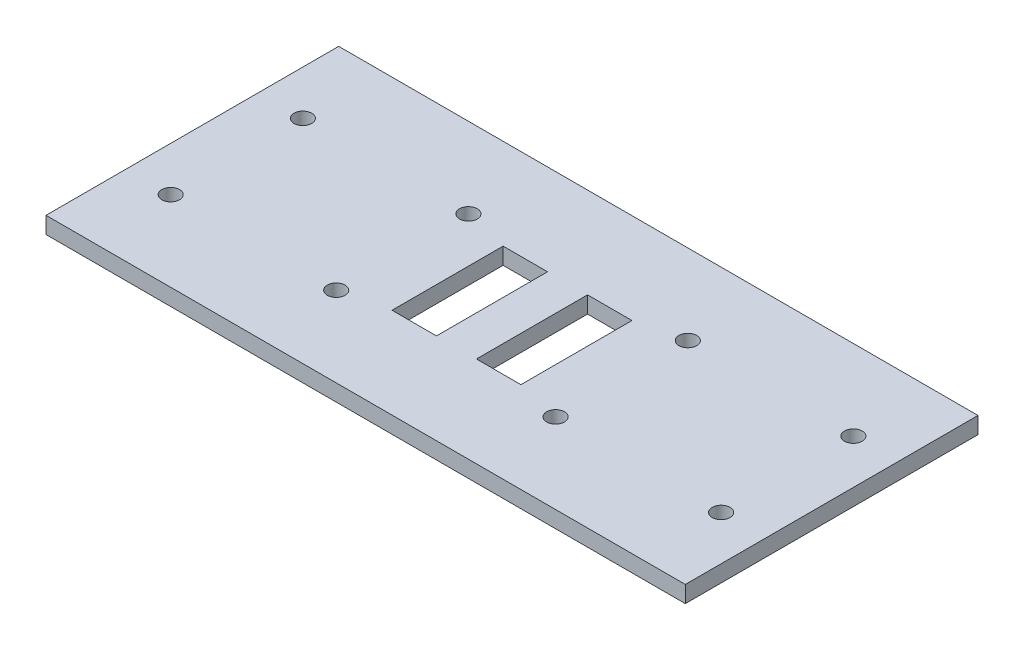
SolidWorks part; units mm, degrees
ref_plane "Plano frontal" through (0, 0, 0) normal (0, 0, 1) x (1, 0, 0)
ref_plane "Plano superior" through (0, 0, 0) normal (0, 1, 0) x (1, 0, 0)
ref_plane "Plano direito" through (0, 0, 0) normal (1, 0, 0) x (0, 0, -1)
sketch "Esboço1" plane through (0, 0, 0) normal (0, 1, 0) x (1, 0, 0)
  line L7 (-57.5484, 26.3464) -> (57.5484, 26.3464)
  line L8 (57.5484, 26.3464) -> (57.5484, -26.3464)
  line L9 (57.5484, -26.3464) -> (-57.5484, -26.3464)
  line L10 (-57.5484, -26.3464) -> (-57.5484, 26.3464)
  line L11 (0, 26.3464) -> (0, -26.3464) construction
  line L12 (-57.5484, 0) -> (57.5484, 0) construction
extrude "Ressalto-extrusão1" add sketch "Esboço1" along normal blind 3
sketch "Esboço2" plane through (0, 3, 0) normal (0, 1, 0) x (1, 0, 0)
  line L0 (0, 26.3464) -> (0, -26.3464) construction
  line L1 (57.5484, 26.3464) -> (-57.5484, 26.3464) construction
  line L2 (-57.5484, -26.3464) -> (57.5484, -26.3464) construction
  circle A0 centre (-49.5484, 11.9) radius 1.6
  circle A1 centre (-19.7484, 11.9) radius 1.6
  circle A2 centre (-49.5484, -11.9) radius 1.6
  circle A3 centre (-19.7484, -11.9) radius 1.6
  circle A4 centre (49.5484, -11.9) radius 1.6
  circle A5 centre (19.7484, -11.9) radius 1.6
  circle A6 centre (19.7484, 11.9) radius 1.6
  circle A7 centre (49.5484, 11.9) radius 1.6
extrude "Corte-extrusão1" cut sketch "Esboço2" against normal through all
sketch "Esboço3" plane through (0, 3, 0) normal (0, 1, 0) x (1, 0, 0)
  line L0 (-13.3484, 18.5) -> (-1.8484, 18.5) construction
  line L1 (-1.8484, 18.5) -> (-1.8484, -18.5) construction
  line L2 (-11.5984, 10) -> (-3.5984, 10)
  line L3 (-3.5984, 10) -> (-3.5984, -10)
  line L4 (-3.5984, -10) -> (-11.5984, -10)
  line L5 (-11.5984, -10) -> (-11.5984, 10)
  line L7 (0, 0) -> (0, -26.3464) construction
  line L8 (-57.5484, -26.3464) -> (57.5484, -26.3464) construction
  line L9 (3.5984, -10) -> (11.5984, -10)
  line L10 (3.5984, 10) -> (3.5984, -10)
  line L11 (11.5984, -10) -> (11.5984, 10)
  line L12 (11.5984, 10) -> (3.5984, 10)
  point P8 (-3.5984, 0)
  point P11 (-7.5984, 10)
  dimension "D1" = 8
  dimension "D2" = 20
  dimension "D3" = 18.5
  dimension "D4" = 5.75
extrude "Corte-extrusão2" cut sketch "Esboço3" against normal through all
